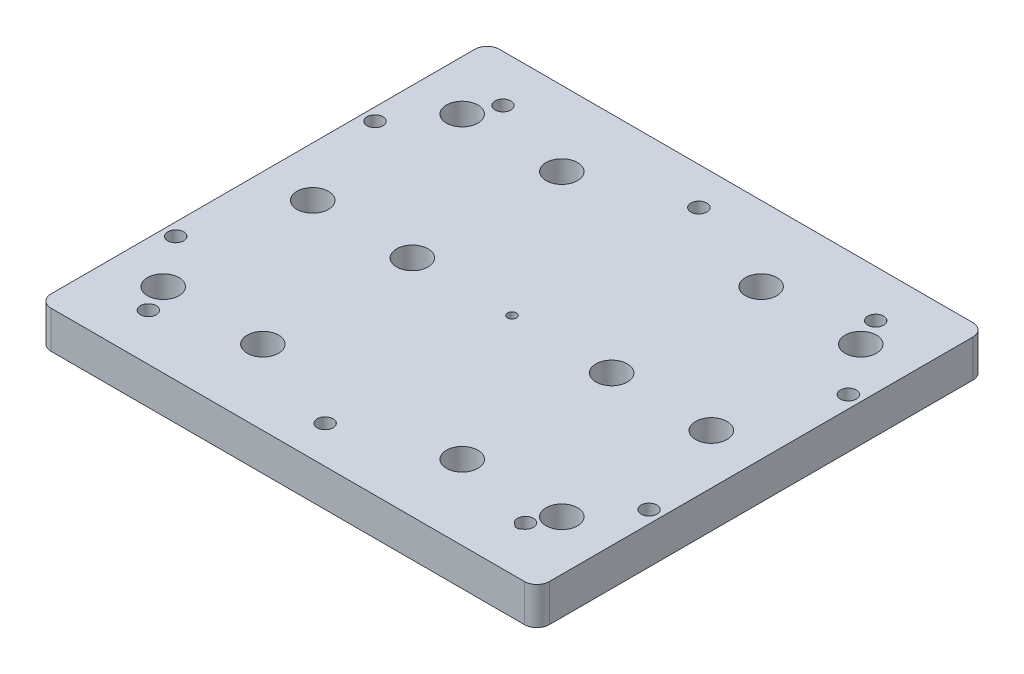
SolidWorks part; units mm, degrees
material "6061-T6 (SS)"
ref_plane "Front Plane" through (0, 0, 0) normal (0, 0, 1) x (1, 0, 0)
ref_plane "Top Plane" through (0, 0, 0) normal (0, 1, 0) x (1, 0, 0)
ref_plane "Right Plane" through (0, 0, 0) normal (1, 0, 0) x (0, 0, -1)
sketch "Sketch1" plane through (0, 0, 0) normal (0, 1, 0) x (1, 0, 0)
  line L1 (63.5, 57.15) -> (-63.5, 57.15)
  line L2 (63.5, 57.15) -> (63.5, -57.15)
  line L3 (63.5, -57.15) -> (-63.5, -57.15)
  line L4 (-63.5, 57.15) -> (-63.5, -57.15)
  line L5 (63.5, 57.15) -> (-63.5, -57.15) construction
  line L6 (63.5, -57.15) -> (-63.5, 57.15) construction
  point P0 (0, 0)
  dimension "D1" = 127
  dimension "D2" = 114.3
extrude "stock" add sketch "Sketch1" along normal blind 9.525
hole_wizard "NUC standoffs" positions "Sketch2" profile "Sketch3" tap size "#4-40" standard "ANSI Inch" end condition through all
sketch "Sketch2" plane through (0, 9.525, 0) normal (0, 1, 0) x (1, 0, 0)
  line L1 (-47.5, -45.2) -> (47.5, -45.2)
  line L2 (-47.5, -45.2) -> (-47.5, 45.2)
  line L3 (-47.5, 45.2) -> (47.5, 45.2)
  line L4 (47.5, -45.2) -> (47.5, 45.2)
  line L5 (-47.5, -45.2) -> (47.5, 45.2) construction
  line L6 (-47.5, 45.2) -> (47.5, -45.2) construction
  point P0 (-47.5, 45.2)
  point P2 (-47.5, -45.2)
  point P4 (47.5, -45.2)
  point P6 (47.5, 45.2)
  point P9 (0, 0)
  dimension "D1" = 95
  dimension "D2" = 90.4
sketch "Sketch3" plane through (-47.5, 9.525, -45.2) normal (1, 0, 0) x (0, 0, 1)
  line L0 (0, 0) -> (0, 9.525)
  line L1 (0, 9.525) -> (1.1303, 9.525)
  line L2 (1.1303, 9.525) -> (1.1303, 0)
  line L5 (1.1303, 0) -> (0, 0)
  line L11 (0, -6.35) -> (0, 107.95) construction
  dimension "Thru Tap Drill Dia." = 2.2606
  dimension "Thru Tap Drill Depth" = 9.525
cosmetic thread "Hole Thread1" parameters "D2"=2.8448
cosmetic thread "Hole Thread2" parameters "D2"=2.8448
cosmetic thread "Hole Thread3" parameters "D2"=2.8448
cosmetic thread "Hole Thread4" parameters "D2"=2.8448
cosmetic thread "Hole Thread17" parameters "D2"=2.8448
hole_wizard "Cover mount" positions "Sketch6" profile "Sketch7" tap size "#4-40" standard "ANSI Inch" end condition through all
sketch "Sketch6" plane through (0, 9.525, 0) normal (0, 1, 0) x (1, 0, 0)
  line L1 (60.325, 25.4) -> (-60.325, 25.4)
  line L2 (60.325, 25.4) -> (60.325, -25.4)
  line L3 (60.325, -25.4) -> (-60.325, -25.4)
  line L4 (-60.325, 25.4) -> (-60.325, -25.4)
  line L5 (60.325, 25.4) -> (-60.325, -25.4) construction
  line L6 (60.325, -25.4) -> (-60.325, 25.4) construction
  point P0 (60.325, 25.4)
  point P2 (60.325, -25.4)
  point P4 (-60.325, -25.4)
  point P6 (-60.325, 25.4)
  point P8 (0, 0)
  dimension "D1" = 120.65
  dimension "D2" = 50.8
sketch "Sketch7" plane through (60.325, 9.525, -25.4) normal (1, 0, 0) x (0, 0, 1)
  line L0 (0, 0) -> (0, 9.525)
  line L1 (0, 9.525) -> (1.1303, 9.525)
  line L2 (1.1303, 9.525) -> (1.1303, 0)
  line L5 (1.1303, 0) -> (0, 0)
  line L11 (0, -6.35) -> (0, 107.95) construction
  dimension "Thru Tap Drill Dia." = 2.2606
  dimension "Thru Tap Drill Depth" = 9.525
cosmetic thread "Hole Thread11" parameters "D2"=2.8448
cosmetic thread "Hole Thread12" parameters "D2"=2.8448
cosmetic thread "Hole Thread13" parameters "D2"=2.8448
cosmetic thread "Hole Thread14" parameters "D2"=2.8448
fillet "Fillet1" radius 3.175 4 edges at (63.5, 4.7625, -57.15) (-63.5, 4.7625, -57.15) (63.5, 4.7625, 57.15) (-63.5, 4.7625, 57.15)
hole_wizard "lidar box mount" positions "Sketch8" profile "Sketch9" tap size "#4-40" standard "ANSI Inch" end condition through all
sketch "Sketch8" plane through (0, 9.525, 0) normal (0, 1, 0) x (1, 0, 0)
  line L0 (0, 47.625) -> (0, -47.625) construction
  line L1 (-63.5, 0) -> (63.5, 0) construction
  line L2 (-63.5, 53.975) -> (-63.5, -53.975) construction
  line L3 (63.5, -53.975) -> (63.5, 53.975) construction
  point P0 (0, -47.625)
  point P2 (0, 47.625)
  point P16 (0, 0)
  point P17 (0, 0)
  dimension "D1" = 95.25
sketch "Sketch9" plane through (0, 9.525, 47.625) normal (1, 0, 0) x (0, 0, 1)
  line L0 (0, 0) -> (0, 9.525)
  line L1 (0, 9.525) -> (1.1303, 9.525)
  line L2 (1.1303, 9.525) -> (1.1303, 0)
  line L5 (1.1303, 0) -> (0, 0)
  line L11 (0, -6.35) -> (0, 107.95) construction
  dimension "Thru Tap Drill Dia." = 2.2606
  dimension "Thru Tap Drill Depth" = 9.525
cosmetic thread "Hole Thread15" parameters "D2"=2.8448
cosmetic thread "Hole Thread16" parameters "D2"=2.8448
hole_wizard "1/4-20 Tapped Hole1" positions "3DSketch1" profile "Sketch10" tap size "1/4-20" standard "ANSI Inch" end condition up to next
sketch3d "3DSketch1"
  line L0 (50.8, 0, -38.1) -> (25.4, 0, -38.1) construction
  line L1 (25.4, 0, 0) -> (50.8, 0, 0) construction
  line L2 (50.8, 0, 38.1) -> (25.4, 0, 38.1) construction
  line L3 (38.1, 0, 38.1) -> (38.1, 0, -38.1) construction
  line L4 (-25.4, 0, -38.1) -> (-50.8, 0, -38.1) construction
  line L5 (-50.8, 0, 0) -> (-25.4, 0, 0) construction
  line L6 (-25.4, 0, 38.1) -> (-50.8, 0, 38.1) construction
  line L7 (-38.1, 0, 38.1) -> (-38.1, 0, -38.1) construction
  line L8 (-25.4, 0, 0) -> (25.4, 0, 0) construction
  point P0 (50.8, 0, -38.1)
  point P2 (25.4, 0, -38.1)
  point P4 (25.4, 0, 0)
  point P6 (50.8, 0, 0)
  point P8 (50.8, 0, 38.1)
  point P10 (25.4, 0, 38.1)
  point P12 (-25.4, 0, 38.1)
  point P14 (-50.8, 0, 38.1)
  point P16 (-50.8, 0, 0)
  point P18 (-25.4, 0, 0)
  point P20 (-25.4, 0, -38.1)
  point P22 (-50.8, 0, -38.1)
  point P41 (-38.1, 0, 0)
  point P42 (38.1, 0, 0)
  point P46 (0, 0, 0)
  point P48 (38.1, 0, 0)
  point P49 (-38.1, 0, 0)
  dimension "D1" = 76.2
  dimension "D2" = 76.2
  dimension "D3" = 25.4
sketch "Sketch10" plane through (50.8, 0, -38.1) normal (1, 0, 0) x (0, 0, -1)
  line L0 (0, 0) -> (0, 9.525)
  line L1 (0, 9.525) -> (2.5527, 9.525)
  line L2 (2.5527, 9.525) -> (2.5527, 0)
  line L5 (2.5527, 0) -> (0, 0)
  line L11 (0, -6.35) -> (0, 107.95) construction
  dimension "Thru Tap Drill Dia." = 5.1054
  dimension "Thru Tap Drill Depth" = 9.525
cosmetic thread "Hole Thread18" parameters "D2"=6.35
cosmetic thread "Hole Thread19" parameters "D2"=6.35
cosmetic thread "Hole Thread20" parameters "D2"=6.35
cosmetic thread "Hole Thread21" parameters "D2"=6.35
cosmetic thread "Hole Thread22" parameters "D2"=6.35
cosmetic thread "Hole Thread23" parameters "D2"=6.35
cosmetic thread "Hole Thread24" parameters "D2"=6.35
cosmetic thread "Hole Thread25" parameters "D2"=6.35
cosmetic thread "Hole Thread26" parameters "D2"=6.35
cosmetic thread "Hole Thread27" parameters "D2"=6.35
cosmetic thread "Hole Thread28" parameters "D2"=6.35
cosmetic thread "Hole Thread29" parameters "D2"=6.35
hole_wizard "#21 (0.159) Diameter Hole1" positions "Sketch11" profile "Sketch12" hole size "#21" standard "ANSI Inch" end condition up to next
sketch "Sketch11" plane through (0, 0, 0) normal (0, -1, 0) x (-1, 0, 0)
  circle A0 centre (-47.5, -45.2) radius 1.1303 construction
  point P0 (-47.5, 45.2)
  point P3 (-60.325, 25.4)
  point P6 (-60.325, -25.4)
  point P9 (-47.5, -44.0697)
  point P13 (0, -47.625)
  point P16 (47.5, -45.2)
  point P19 (60.325, -25.4)
  point P22 (60.325, 25.4)
  point P25 (47.5, 45.2)
  point P27 (0, 47.625)
sketch "Sketch12" plane through (47.5, 0, -45.2) normal (1, 0, 0) x (0, 0, -1)
  line L0 (0, 0) -> (0, 9.525)
  line L1 (0, 9.525) -> (2.0193, 9.525)
  line L2 (2.0193, 9.525) -> (2.0193, 0)
  line L5 (2.0193, 0) -> (0, 0)
  line L11 (0, -6.35) -> (0, 107.95) construction
  dimension "Thru Hole Dia." = 4.0386
  dimension "Thru Hole Depth" = 9.525
hole_wizard "O (0.316) Diameter Hole1" positions "Sketch13" profile "Sketch14" hole size "O" standard "ANSI Inch" end condition up to next
sketch "Sketch13" plane through (0, 0, 0) normal (0, -1, 0) x (-1, 0, 0)
  point P3 (-50.8, 38.1)
  point P6 (-25.4, 38.1)
  point P9 (-25.4, 0)
  point P12 (-50.8, 0)
  point P15 (-50.8, -38.1)
  point P18 (-25.4, -38.1)
  point P21 (25.4, -38.1)
  point P23 (50.8, -38.1)
  point P26 (50.8, 0)
  point P29 (25.4, 0)
  point P32 (25.4, 38.1)
  point P38 (50.8, 38.1)
sketch "Sketch14" plane through (50.8, 0, -38.1) normal (1, 0, 0) x (0, 0, -1)
  line L0 (0, 0) -> (0, 9.525)
  line L1 (0, 9.525) -> (4.0132, 9.525)
  line L2 (4.0132, 9.525) -> (4.0132, 0)
  line L5 (4.0132, 0) -> (0, 0)
  line L11 (0, -6.35) -> (0, 107.95) construction
  dimension "Thru Hole Dia." = 8.0264
  dimension "Thru Hole Depth" = 9.525
equation "\"D1@Sketch2\"=95mm"
equation "\"D2@Sketch2\"=90.4mm"
